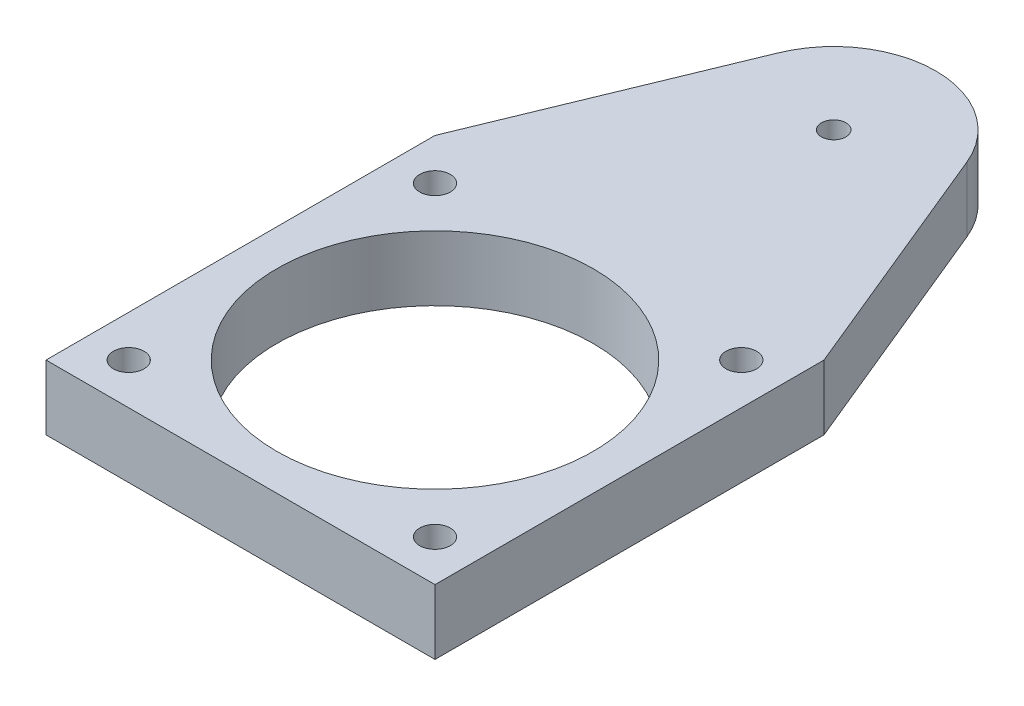
SolidWorks part; units mm, degrees
ref_plane "Front Plane" through (0, 0, 0) normal (0, 0, 1) x (1, 0, 0)
ref_plane "Top Plane" through (0, 0, 0) normal (0, 1, 0) x (1, 0, 0)
ref_plane "Right Plane" through (0, 0, 0) normal (1, 0, 0) x (0, 0, -1)
sketch "Sketch1" plane through (0, 0, 0) normal (0, 1, 0) x (1, 0, 0)
  line L0 (4.05, 4.05) -> (34.05, 4.05) construction
  line L1 (0, 0) -> (38.1, 0)
  line L2 (0, 0) -> (0, 38.1)
  line L4 (38.1, 0) -> (38.1, 38.1)
  line L5 (4.05, 34.05) -> (4.05, 4.05) construction
  line L6 (0, 38.1) -> (9.8032, 61.9075)
  line L8 (28.2968, 61.9075) -> (38.1, 38.1)
  circle A0 centre (4.05, 4.05) radius 1.5
  circle A1 centre (34.05, 4.05) radius 1.5
  circle A2 centre (34.05, 34.05) radius 1.5
  circle A3 centre (4.05, 34.05) radius 1.5
  circle A4 centre (19.05, 19.05) radius 15.5
  circle A5 centre (19.05, 58.1) radius 1.2
  arc A6 (9.8032, 61.9075) -> (28.2968, 61.9075) centre (19.05, 58.1) cw
  point P7 (19.05, 4.05)
  point P8 (0, 19.05)
  point P16 (19.05, 0)
  point P18 (4.05, 19.05)
  dimension "D5" = 3
  dimension "D6" = 30
  dimension "D8" = 31
  dimension "D9" = 2.4
  dimension "D10" = 10
  dimension "D1" = 38.1
  dimension "D2" = 19.05
  dimension "D7" = 30
  dimension "D11" = 20
  dimension "D12" = 38.1
  dimension "D3" = 2
  dimension "D4" = 2
extrude "Boss-Extrude1" add sketch "Sketch1" along normal blind 6.35
